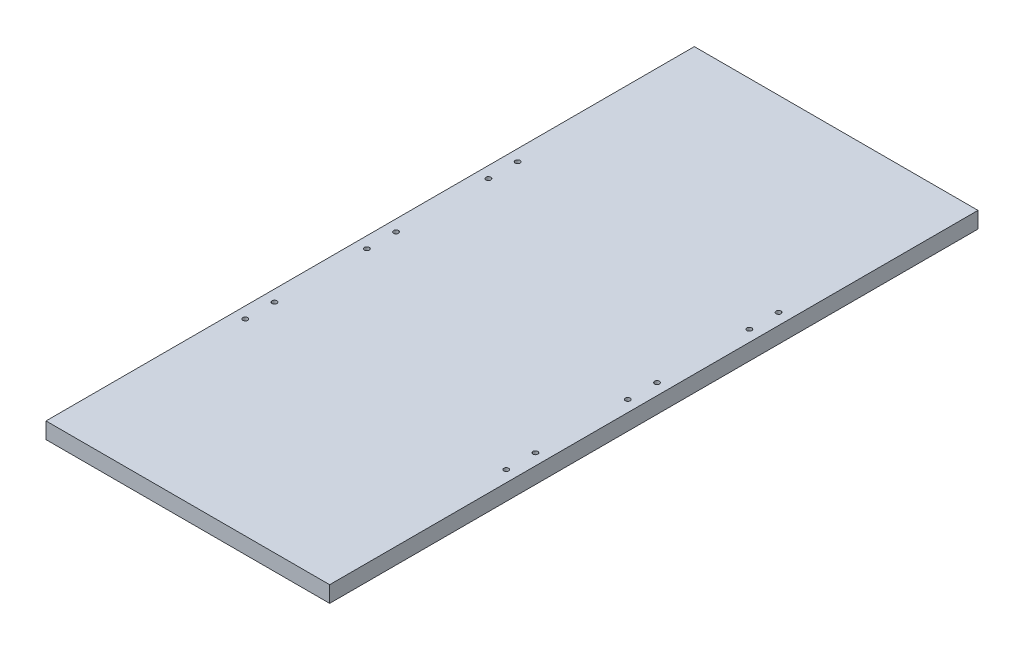
SolidWorks part; units mm, degrees
ref_plane "前视基准面" through (0, 0, 0) normal (0, 0, 1) x (1, 0, 0)
ref_plane "上视基准面" through (0, 0, 0) normal (0, 1, 0) x (1, 0, 0)
ref_plane "右视基准面" through (0, 0, 0) normal (1, 0, 0) x (0, 0, -1)
sketch "草图1" plane through (0, 0, 0) normal (0, 1, 0) x (1, 0, 0)
  line L1 (-87.5, 200) -> (87.5, 200)
  line L2 (-87.5, 200) -> (-87.5, -200)
  line L3 (-87.5, -200) -> (87.5, -200)
  line L4 (87.5, 200) -> (87.5, -200)
  line L5 (-87.5, 200) -> (87.5, -200) construction
  line L6 (-87.5, -200) -> (87.5, 200) construction
  point P0 (0, 0)
  dimension "D1" = 175
  dimension "D2" = 400
extrude "凸台-拉伸1" add sketch "草图1" along normal blind 10
sketch "草图3" plane through (0, 0, 0) normal (0, -1, 0) x (1, 0, 0)
  line L0 (-80.5, -83.96) -> (-80.5, -65.96) construction
  line L1 (-80.5, -65.96) -> (-80.5, -8.96) construction
  line L2 (-80.5, -8.96) -> (-80.5, 9.04) construction
  line L3 (-80.5, 9.04) -> (-80.5, 66.04) construction
  line L4 (-80.5, 66.04) -> (-80.5, 84.04) construction
  line L5 (-87.5, 200) -> (87.5, 200) construction
  line L6 (-87.5, -200) -> (-87.5, 200) construction
  circle A0 centre (-80.5, -83.96) radius 1.5
  circle A1 centre (-80.5, -65.96) radius 1.5
  circle A2 centre (-80.5, -8.96) radius 1.5
  circle A3 centre (-80.5, 9.04) radius 1.5
  circle A4 centre (-80.5, 66.04) radius 1.5
  circle A5 centre (-80.5, 84.04) radius 1.5
  dimension "D1" = 3
  dimension "D2" = 3
  dimension "D3" = 3
  dimension "D4" = 3
  dimension "D5" = 3
  dimension "D6" = 3
  dimension "D7" = 283.96
  dimension "D8" = 7
  dimension "D9" = 57
  dimension "D10" = 57
  dimension "D11" = 18
  dimension "D12" = 18
  dimension "D13" = 18
extrude "切除-拉伸1" cut sketch "草图3" against normal blind 10
mirror "镜向1" about plane through (0, 0, 0) normal (1, 0, 0) of "切除-拉伸1"
